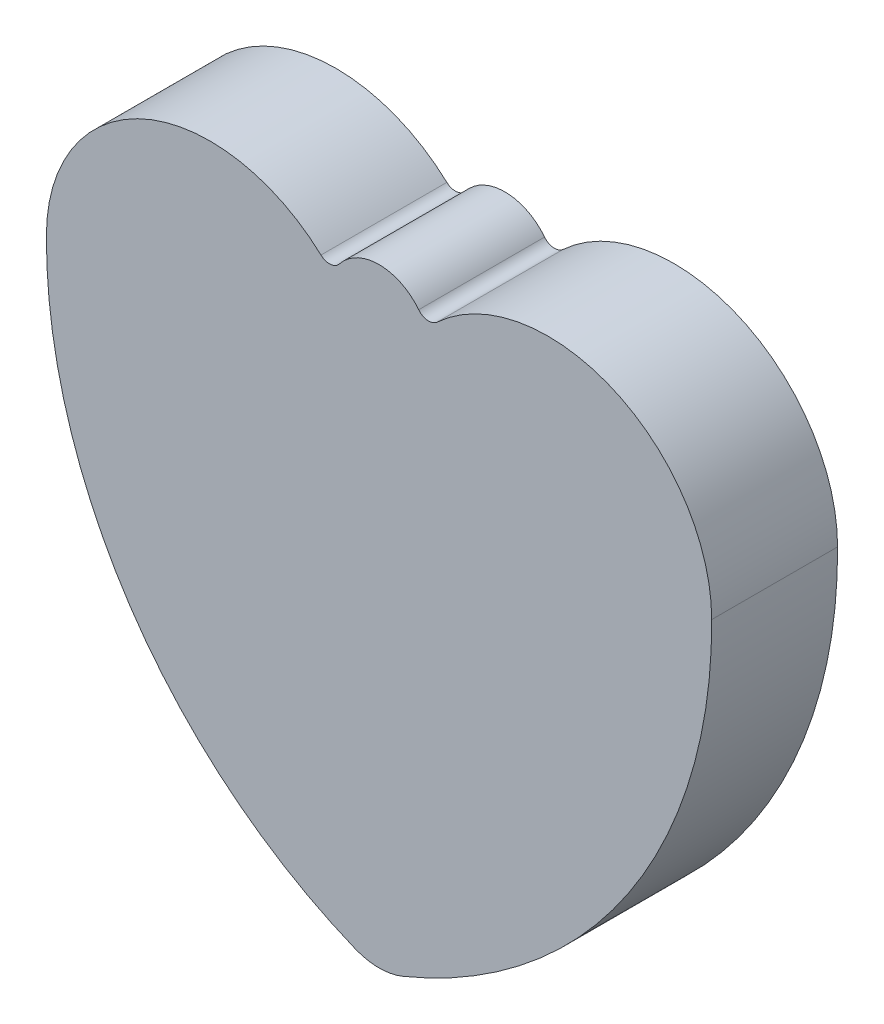
SolidWorks part; units mm, degrees
ref_plane "Płaszczyzna przednia" through (0, 0, 0) normal (0, 0, 1) x (1, 0, 0)
ref_plane "Płaszczyzna górna" through (0, 0, 0) normal (0, 1, 0) x (1, 0, 0)
ref_plane "Płaszczyzna prawa" through (0, 0, 0) normal (1, 0, 0) x (0, 0, -1)
sketch "Szkic1" plane through (0, 0, 0) normal (0, 0, 1) x (1, 0, 0)
  arc A0 (-4.6153, 22.7432) -> (-26.4259, 13.1842) centre (-13.4259, 13.1842) ccw
  arc A1 (4.6153, 22.7432) -> (26.4259, 13.1842) centre (13.4259, 13.1842) cw
  arc A2 (-1.8963, -23.6265) -> (-26.4259, 13.1842) centre (13.0914, 12.9391) cw
  arc A3 (1.8963, -23.6265) -> (26.4259, 13.1842) centre (-13.0914, 12.9391) ccw
  arc A5 (1.8963, -23.6265) -> (-1.8963, -23.6265) centre (0, -19) cw
  arc A6 (-3.1501, 22.8622) -> (3.1501, 22.8622) centre (0, 20.397) cw
  arc A7 (4.6153, 22.7432) -> (3.1501, 22.8622) centre (3.9376, 23.4785) cw
  arc A8 (-3.1501, 22.8622) -> (-4.6153, 22.7432) centre (-3.9376, 23.4785) cw
  point P0 (0, 0)
  dimension "D1" = 1
  dimension "D2" = 5
extrude "Dodanie-wyciągnięcie1" add sketch "Szkic1" along normal blind 10
scale "Skala1" scale about centroid uniform scaling yes scale factor 0.9
